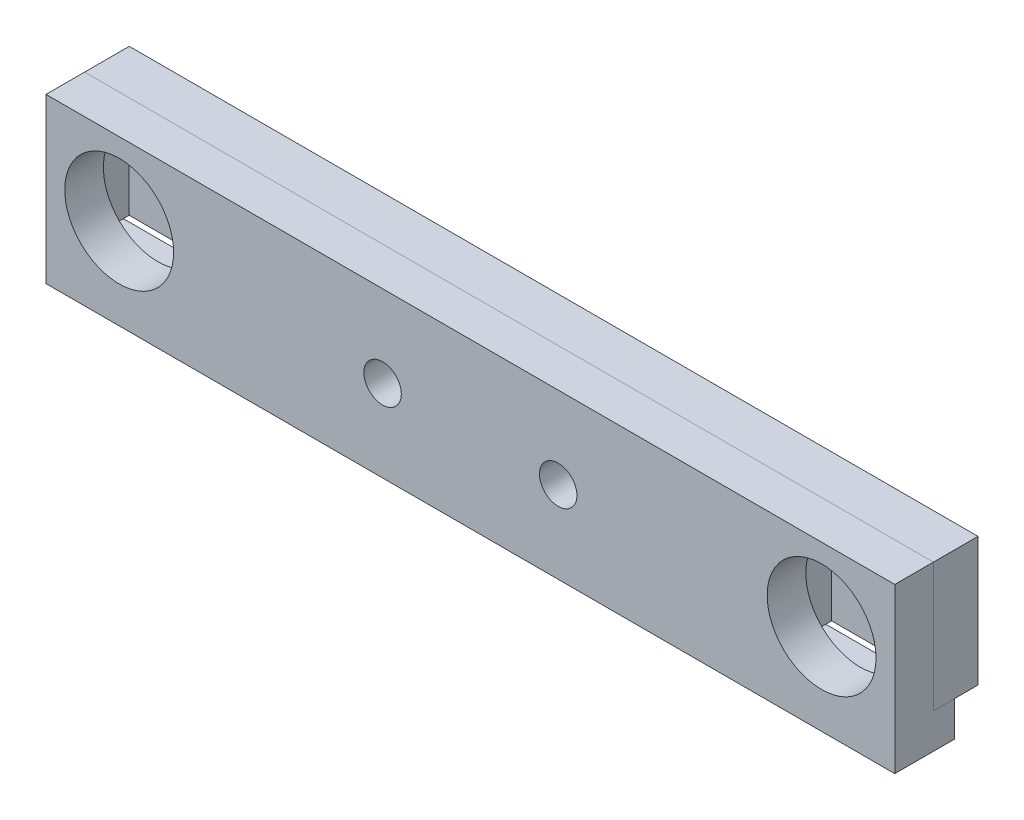
SolidWorks part; units mm, degrees
ref_plane "Front Plane" through (0, 0, 0) normal (0, 0, 1) x (1, 0, 0)
ref_plane "Top Plane" through (0, 0, 0) normal (0, 1, 0) x (1, 0, 0)
ref_plane "Right Plane" through (0, 0, 0) normal (1, 0, 0) x (0, 0, -1)
sketch "Sketch1" plane through (0, 0, 0) normal (0, 0, 1) x (1, 0, 0)
  line L1 (0, 0) -> (72.5, 0)
  line L2 (0, 0) -> (0, 11)
  line L3 (0, 11) -> (72.5, 11)
  line L4 (72.5, 0) -> (72.5, 11)
  line L5 (0, 0) -> (72.5, 11) construction
  line L6 (0, 11) -> (72.5, 0) construction
  point P4 (57.7044, 10.2683)
  point P5 (0, 0)
  point P7 (64.2095, 19.5843)
  point P8 (0, 0)
  point P10 (0, 0)
  point P11 (56.9059, 14.034)
  point P12 (56.9059, 0)
  point P13 (72.5, 12.3089)
  dimension "D1" = 72.5
  dimension "D2" = 11
extrude "Boss-Extrude1" add sketch "Sketch1" along normal blind 1.5
sketch "Sketch2" plane through (0, 0, 1.5) normal (0, 0, 1) x (1, 0, 0)
  line L0 (0, 0) -> (72.5, 0) construction
  line L1 (1.5, 9.5) -> (11, 9.5)
  line L2 (1.5, 9.5) -> (1.5, 0)
  line L4 (11, 9.5) -> (11, 0)
  line L5 (1.5, 9.5) -> (11, 0) construction
  line L6 (1.5, 0) -> (11, 9.5) construction
  line L7 (61.5, 9.5) -> (61.5, 0)
  line L8 (61.5, 9.5) -> (71, 9.5)
  line L9 (71, 9.5) -> (71, 0)
  line L11 (11, 0) -> (61.5, 0)
  line L12 (71, 0) -> (72.5, 0)
  line L15 (0, 11) -> (0, 0)
  line L16 (0, 0) -> (72.5, 0)
  line L17 (72.5, 0) -> (72.5, 11)
  line L18 (72.5, 11) -> (0, 11)
  line L19 (0, 11) -> (0, 0)
  line L20 (0, 0) -> (1.5, 0)
  line L21 (72.5, 0) -> (72.5, 11)
  line L22 (72.5, 11) -> (0, 11)
  point P5 (0, 0)
  point P13 (0.5379, 9.5)
  point P15 (1.8927, 9.5)
  point P17 (0, 0)
  dimension "D1" = 9.5
  dimension "D4" = 1.5
  dimension "D5" = 50.5
  dimension "D3" = 0
  dimension "D2" = 2
extrude "Boss-Extrude2" add sketch "Sketch2" along normal blind 2.31
sketch "Sketch3" plane through (0, 0, 3.81) normal (0, 0, 1) x (1, 0, 0)
  line L0 (1.5, 9.5) -> (11, 0) construction
  line L2 (0, 11) -> (72.5, 11)
  line L3 (0, 11) -> (0, -3)
  line L4 (0, -3) -> (72.5, -3)
  line L5 (72.5, 11) -> (72.5, -3)
  line L6 (0, 11) -> (72.5, -3) construction
  line L7 (0, -3) -> (72.5, 11) construction
  line L8 (71, 0) -> (72.5, 0) construction
  circle A0 centre (6.25, 4.75) radius 4.65
  circle A1 centre (66.25, 4.75) radius 4.65
  point P10 (6.25, 4.75)
  point P13 (0, 0)
  point P14 (0, 0)
  point P15 (10.5091, 14.121)
  point P17 (0, 0)
  point P20 (0, 0)
  point P21 (0, 0)
  point P22 (1.0865, -9.4136)
  point P23 (0, 0)
  dimension "D1" = 9.3
  dimension "D2" = 60
  dimension "D3" = 3
extrude "Boss-Extrude3" add sketch "Sketch3" along normal blind 3.3 separate body
sketch "Sketch4" plane through (0, 0, 3.81) normal (0, 0, -1) x (-1, 0, 0)
  line L1 (-72.5, -3) -> (0, -3)
  line L2 (-72.5, -3) -> (-72.5, 0)
  line L3 (-72.5, 0) -> (0, 0)
  line L4 (0, -3) -> (0, 0)
  line L5 (-72.5, -3) -> (0, 0) construction
  line L6 (-72.5, 0) -> (0, -3) construction
  point P4 (0, 0)
  point P5 (0, 0)
  point P7 (-70.6073, 25.4327)
  point P8 (0, 0)
  point P10 (0, 0)
extrude "Boss-Extrude4" add sketch "Sketch4" along normal offset from surface (1.81 mm away) 0.5 up to face at (66.25, 4.75, 1.5)
sketch "Sketch5" plane through (0, 0, 7.11) normal (0, 0, 1) x (1, 0, 0)
  line L0 (28.75, 4) -> (43.75, 4) construction
  line L1 (36.25, -3) -> (36.25, 11) construction
  line L2 (72.5, 11) -> (0, 11) construction
  line L3 (0, -3) -> (72.5, -3) construction
  circle A0 centre (28.75, 4) radius 1.6
  circle A1 centre (43.75, 4) radius 1.6
  point P6 (36.25, 9.4844)
  point P9 (0, 0)
  point P12 (36.25, 4)
  point P13 (52.691, -3)
  point P14 (36.25, -3)
  point P15 (0, 0)
  point P16 (43.8208, 11)
  point P17 (36.25, 11)
  dimension "D1" = 3.2
  dimension "D2" = 15
extrude "Cut-Extrude1" cut sketch "Sketch5" against normal through all
